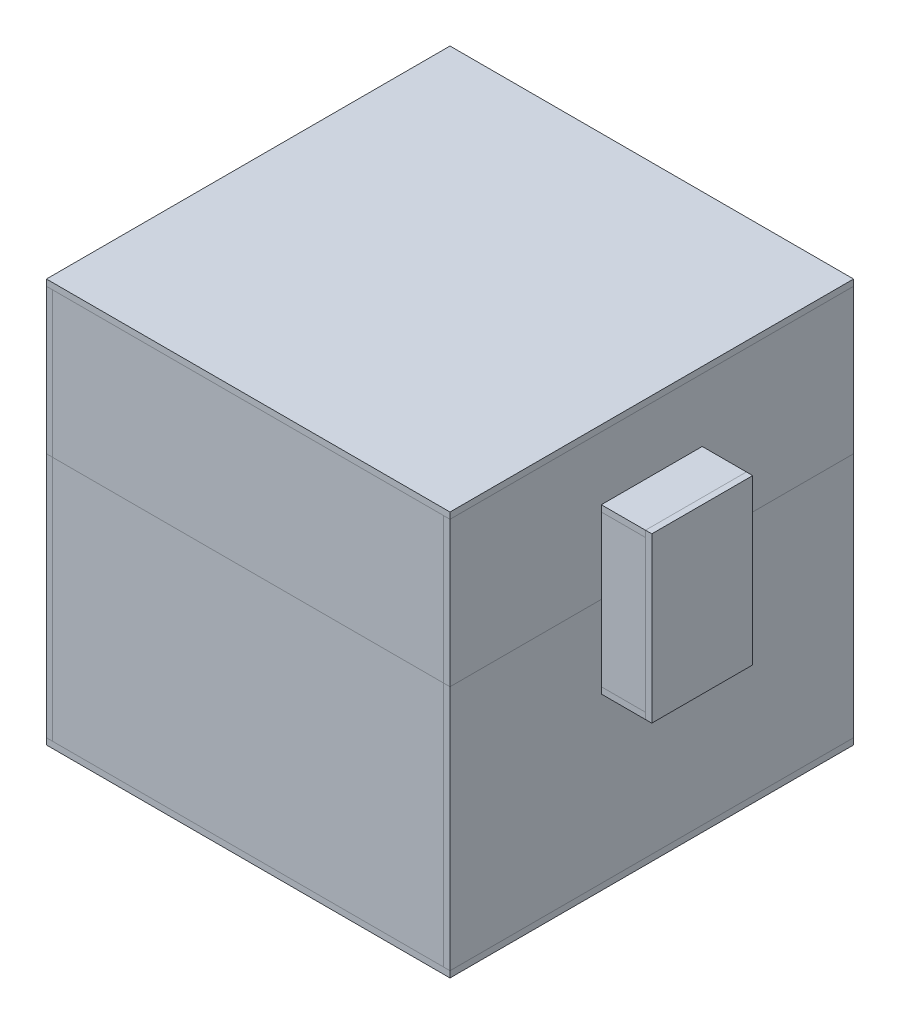
SolidWorks part; units mm, degrees
ref_plane "Front Plane" through (0, 0, 0) normal (0, 0, 1) x (1, 0, 0)
ref_plane "Top Plane" through (0, 0, 0) normal (0, 1, 0) x (1, 0, 0)
ref_plane "Right Plane" through (0, 0, 0) normal (1, 0, 0) x (0, 0, -1)
sketch "Sketch1" plane through (0, 0, 0) normal (0, 1, 0) x (1, 0, 0)
  line L1 (-101.6, -101.6) -> (101.6, -101.6)
  line L2 (-101.6, -101.6) -> (-101.6, 101.6)
  line L3 (-101.6, 101.6) -> (101.6, 101.6)
  line L4 (101.6, -101.6) -> (101.6, 101.6)
  line L5 (-101.6, -101.6) -> (101.6, 101.6) construction
  line L6 (-101.6, 101.6) -> (101.6, -101.6) construction
  point P0 (0, 0)
  dimension "D1" = 203.2
extrude "Boss-Extrude1" add sketch "Sketch1" along normal blind 127
sketch "Sketch2" plane through (0, 127, 0) normal (0, 1, 0) x (1, 0, 0)
  line L20 (95.25, -95.25) -> (95.25, 95.25)
  line L21 (95.25, 95.25) -> (-95.25, 95.25)
  line L22 (-95.25, 95.25) -> (-95.25, -95.25)
  line L23 (-95.25, -95.25) -> (95.25, -95.25)
  line L24 (95.25, -95.25) -> (95.25, 95.25)
  line L25 (95.25, 95.25) -> (-95.25, 95.25)
  line L26 (-95.25, 95.25) -> (-95.25, -95.25)
  line L27 (-95.25, -95.25) -> (95.25, -95.25)
  dimension "D1" = 6.35
extrude "Cut-Extrude1" cut sketch "Sketch2" against normal blind 120.65
sketch "Sketch3" plane through (0, 127, 0) normal (0, 1, 0) x (1, 0, 0)
  line L0 (-101.6, -101.6) -> (101.6, -101.6) construction
  line L1 (101.6, -101.6) -> (101.6, 101.6) construction
  line L2 (-101.6, 101.6) -> (-101.6, -101.6) construction
  line L3 (101.6, 101.6) -> (-101.6, 101.6) construction
  line L4 (-101.6, -101.6) -> (101.6, -101.6)
  line L5 (101.6, -101.6) -> (101.6, 101.6)
  line L6 (-101.6, 101.6) -> (-101.6, -101.6)
  line L7 (101.6, 101.6) -> (-101.6, 101.6)
extrude "Boss-Extrude2" add sketch "Sketch3" along normal blind 76.2 separate body
ref_plane "Plane1" through (-101.6, 127, 101.6) normal (1, 0, 0) x (0, 0, -1)
sketch "Sketch5" plane through (0, 203.2, 0) normal (0, 1, 0) x (1, 0, 0)
  line L8 (-95.25, 95.25) -> (-95.25, -95.25)
  line L9 (-95.25, -95.25) -> (95.25, -95.25)
  line L10 (95.25, -95.25) -> (95.25, 95.25)
  line L11 (95.25, 95.25) -> (-95.25, 95.25)
  line L12 (-95.25, 95.25) -> (-95.25, -95.25)
  line L13 (-95.25, -95.25) -> (95.25, -95.25)
  line L14 (95.25, -95.25) -> (95.25, 95.25)
  line L15 (95.25, 95.25) -> (-95.25, 95.25)
  dimension "D1" = 6.35
extrude "Cut-Extrude2" cut sketch "Sketch5" against normal blind 69.85 from offset 6.35 offset against normal yes
sketch "Sketch6" plane through (0, 0, 0) normal (1, 0, 0) x (0, 0, -1)
  line L0 (-101.6, 127) -> (101.6, 127) construction
  line L1 (-25.4, 85.725) -> (25.4, 85.725)
  line L2 (-25.4, 85.725) -> (-25.4, 168.275)
  line L3 (-25.4, 168.275) -> (25.4, 168.275)
  line L4 (25.4, 85.725) -> (25.4, 168.275)
  line L5 (-25.4, 85.725) -> (25.4, 168.275) construction
  line L6 (-25.4, 168.275) -> (25.4, 85.725) construction
  point P0 (0, 127)
  dimension "D1" = 50.8
  dimension "D2" = 82.55
extrude "Boss-Extrude3" add sketch "Sketch6" along normal blind 25.4 from surface at 101.6 separate body starting at face at (101.6, 165.1, 0)
sketch "Sketch7" plane through (-101.6, 0, 0) normal (-1, 0, 0) x (0, 0, 1)
  line L0 (-76.2, 140) -> (-49.7, 140) construction
  line L1 (-101.6, 127) -> (101.6, 127) construction
  line L2 (-101.6, 203.2) -> (-101.6, 127) construction
  line L3 (0, -111.76) -> (0, 111.76) construction
  circle A0 centre (-76.2, 140) radius 2.5
  circle A1 centre (-49.7, 140) radius 2.5
  circle A2 centre (49.7, 140) radius 2.5
  circle A3 centre (76.2, 140) radius 2.5
  dimension "D2" = 5
  dimension "D1" = 26.5
  dimension "D3" = 13
  dimension "D4" = 25.4
extrude "Cut-Extrude3" cut sketch "Sketch7" against normal up to next (6.35 mm away)
mirror "Mirror4" about plane through (0, 127, 0) normal (0, -1, 0) of "Cut-Extrude3"
sketch "Sketch9" plane through (101.6, 0, 0) normal (-1, 0, 0) x (0, 0, 1)
  line L8 (-19.05, 161.925) -> (-19.05, 92.075)
  line L9 (-19.05, 92.075) -> (19.05, 92.075)
  line L10 (19.05, 92.075) -> (19.05, 161.925)
  line L11 (19.05, 161.925) -> (-19.05, 161.925)
  line L12 (-19.05, 161.925) -> (-19.05, 92.075)
  line L13 (-19.05, 92.075) -> (19.05, 92.075)
  line L14 (19.05, 92.075) -> (19.05, 161.925)
  line L15 (19.05, 161.925) -> (-19.05, 161.925)
  dimension "D1" = 6.35
extrude "Cut-Extrude4" cut sketch "Sketch9" against normal blind 19.05 contours L12 L13 L14 L15
sketch "Sketch10" plane through (120.65, 0, 0) normal (-1, 0, 0) x (0, 0, 1)
  line L4 (19.05, 161.925) -> (-19.05, 161.925)
  line L5 (-19.05, 161.925) -> (-19.05, 92.075)
  line L6 (-19.05, 92.075) -> (19.05, 92.075)
  line L7 (19.05, 92.075) -> (19.05, 161.925)
  line L8 (19.05, 161.925) -> (-19.05, 161.925) construction
  line L9 (-19.05, 161.925) -> (-19.05, 92.075) construction
  line L10 (-19.05, 92.075) -> (19.05, 92.075) construction
  line L11 (19.05, 92.075) -> (19.05, 161.925) construction
  line L12 (22.225, 165.1) -> (-22.225, 165.1)
  line L13 (-22.225, 165.1) -> (-22.225, 88.9)
  line L14 (-22.225, 88.9) -> (22.225, 88.9)
  line L15 (22.225, 88.9) -> (22.225, 165.1)
  dimension "D1" = 0
  dimension "D2" = 3.175
extrude "Boss-Extrude4" add sketch "Sketch10" along normal blind 22.225 from offset 3.175 separate body offset against normal yes
sketch "Sketch15" plane through (127, 0, 0) normal (1, 0, 0) x (0, 0, -1)
  line L4 (25.4, 85.725) -> (25.4, 168.275)
  line L5 (25.4, 168.275) -> (-25.4, 168.275)
  line L6 (-25.4, 168.275) -> (-25.4, 85.725)
  line L7 (-25.4, 85.725) -> (25.4, 85.725)
  line L8 (25.4, 85.725) -> (25.4, 168.275)
  line L9 (25.4, 168.275) -> (-25.4, 168.275)
  line L10 (-25.4, 168.275) -> (-25.4, 85.725)
  line L11 (-25.4, 85.725) -> (25.4, 85.725)
  dimension "D1" = 0
extrude "Boss-Extrude5" add sketch "Sketch15" against normal blind 3.175 separate body contours L8 L9 L10 L11
sketch "Sketch16" plane through (0, 168.275, 0) normal (0, 1, 0) x (1, 0, 0)
  line L0 (123.825, 25.4) -> (123.825, -25.4) construction
  line L1 (123.825, 25.4) -> (123.825, -25.4)
  line L4 (101.6, 25.4) -> (101.6, -25.4)
  line L5 (101.6, -25.4) -> (127, -25.4)
  line L6 (127, -25.4) -> (127, 25.4)
  line L7 (127, 25.4) -> (101.6, 25.4)
  line L8 (101.6, 25.4) -> (101.6, -25.4)
  line L9 (101.6, -25.4) -> (123.825, -25.4)
  line L11 (123.825, 25.4) -> (101.6, 25.4)
  dimension "D1" = 0
extrude "Boss-Extrude7" add sketch "Sketch16" against normal blind 3.175 separate body contours L8 L9 L1 L11
sketch "Sketch18" plane through (0, 85.725, 0) normal (0, -1, 0) x (1, 0, 0)
  line L4 (101.6, -25.4) -> (123.825, -25.4)
  line L5 (101.6, 25.4) -> (101.6, -25.4)
  line L6 (123.825, 25.4) -> (101.6, 25.4)
  line L7 (123.825, -25.4) -> (123.825, 25.4)
  line L8 (101.6, -25.4) -> (123.825, -25.4)
  line L9 (101.6, 25.4) -> (101.6, -25.4)
  line L10 (123.825, 25.4) -> (101.6, 25.4)
  line L11 (123.825, -25.4) -> (123.825, 25.4)
  dimension "D1" = 0
extrude "Boss-Extrude8" add sketch "Sketch18" against normal blind 3.175 separate body contours L8 L11 L10 L9
sketch "Sketch12" plane through (101.6, 0, 0) normal (-1, 0, 0) x (0, 0, 1)
  line L0 (0, -111.76) -> (0, 111.76) construction
  line L1 (-9.5, 98.425) -> (9.5, 98.425)
  line L2 (-9.5, 98.425) -> (-9.5, 117.425)
  line L3 (-9.5, 117.425) -> (9.5, 117.425)
  line L4 (9.5, 98.425) -> (9.5, 117.425)
  line L5 (-9.5, 98.425) -> (9.5, 117.425) construction
  line L6 (-9.5, 117.425) -> (9.5, 98.425) construction
  line L7 (-19.05, 92.075) -> (19.05, 92.075) construction
  point P0 (0, 107.925)
  dimension "D1" = 19
  dimension "D2" = 6.35
sketch "Sketch13" plane through (101.6, 0, 0) normal (-1, 0, 0) x (0, 0, 1)
  line L0 (0, -111.76) -> (0, 111.76) construction
  line L2 (-9.5, 98.425) -> (9.5, 117.425) construction
  circle A0 centre (0, 107.925) radius 4.25
  point P4 (0, 0)
  dimension "D1" = 8.5
extrude "Cut-Extrude6" cut sketch "Sketch13" against normal blind 3 contours A0
sketch "Sketch19" plane through (0, 0, 25.4) normal (0, 0, 1) x (1, 0, 0)
  line L0 (123.825, 165.1) -> (101.6, 165.1)
  line L1 (101.6, 88.9) -> (123.825, 88.9)
  line L2 (123.825, 165.1) -> (123.825, 88.9)
  line L3 (127, 168.275) -> (127, 85.725) construction
  line L12 (101.6, 168.275) -> (101.6, 85.725)
  line L13 (101.6, 85.725) -> (127, 85.725)
  line L14 (127, 85.725) -> (127, 168.275)
  line L15 (127, 168.275) -> (101.6, 168.275)
  line L16 (101.6, 165.1) -> (101.6, 88.9)
  line L20 (127, 168.275) -> (101.6, 168.275) construction
  line L21 (127, 85.725) -> (101.6, 85.725) construction
  dimension "D2" = 3.175
  dimension "D3" = 3.175
  dimension "D4" = 3.175
  dimension "D1" = 0
sketch "Sketch21" plane through (0, 0, -25.4) normal (0, 0, -1) x (-1, 0, 0)
  line L12 (-101.6, 165.1) -> (-123.825, 165.1)
  line L13 (-101.6, 88.9) -> (-101.6, 165.1)
  line L14 (-123.825, 88.9) -> (-101.6, 88.9)
  line L15 (-123.825, 165.1) -> (-123.825, 88.9)
  line L16 (-101.6, 165.1) -> (-123.825, 165.1)
  line L17 (-101.6, 88.9) -> (-101.6, 165.1)
  line L18 (-123.825, 88.9) -> (-101.6, 88.9)
  line L19 (-123.825, 165.1) -> (-123.825, 88.9)
  dimension "D1" = 0
extrude "Boss-Extrude13" add sketch "Sketch21" against normal blind 3.175 separate body
delete or keep bodies "Body-Delete/Keep 1" type delete bodies bodies 108
sketch "Sketch22" plane through (0, 203.2, 0) normal (0, 1, 0) x (1, 0, 0)
  line L4 (-101.6, 101.6) -> (-101.6, -101.6)
  line L5 (-101.6, -101.6) -> (101.6, -101.6)
  line L6 (101.6, -101.6) -> (101.6, 101.6)
  line L7 (101.6, 101.6) -> (-101.6, 101.6)
  line L8 (-101.6, 101.6) -> (-101.6, -101.6)
  line L9 (-101.6, -101.6) -> (101.6, -101.6)
  line L10 (101.6, -101.6) -> (101.6, 101.6)
  line L11 (101.6, 101.6) -> (-101.6, 101.6)
  dimension "D1" = 0
extrude "Boss-Extrude14" add sketch "Sketch22" against normal blind 3.175 separate body
sketch "Sketch23" plane through (101.6, 0, 0) normal (1, 0, 0) x (0, 0, -1)
  line L0 (101.6, 200.025) -> (-101.6, 200.025)
  line L12 (-101.6, 127) -> (101.6, 127)
  line L13 (101.6, 127) -> (101.6, 203.2)
  line L14 (101.6, 203.2) -> (-101.6, 203.2)
  line L15 (-101.6, 203.2) -> (-101.6, 127)
  line L16 (-101.6, 127) -> (101.6, 127)
  line L17 (101.6, 127) -> (101.6, 200.025)
  line L19 (-101.6, 200.025) -> (-101.6, 127)
  dimension "D1" = 0
extrude "Boss-Extrude16" add sketch "Sketch23" against normal blind 3.175 separate body contours L16 L17 L0 L19
sketch "Sketch24" plane through (-101.6, 0, 0) normal (-1, 0, 0) x (0, 0, 1)
  line L0 (-101.6, 200.025) -> (101.6, 200.025)
  line L4 (-101.6, 127) -> (101.6, 127)
  line L5 (101.6, 127) -> (101.6, 203.2)
  line L6 (101.6, 203.2) -> (-101.6, 203.2)
  line L7 (-101.6, 203.2) -> (-101.6, 127)
  line L8 (-101.6, 127) -> (101.6, 127)
  line L9 (101.6, 127) -> (101.6, 200.025)
  line L11 (-101.6, 200.025) -> (-101.6, 127)
  circle A0 centre (76.2, 140) radius 2.5 construction
  circle A1 centre (49.7, 140) radius 2.5 construction
  circle A2 centre (-49.7, 140) radius 2.5 construction
  circle A3 centre (-76.2, 140) radius 2.5 construction
  circle A4 centre (76.2, 140) radius 2.5
  circle A5 centre (49.7, 140) radius 2.5
  circle A6 centre (-49.7, 140) radius 2.5
  circle A7 centre (-76.2, 140) radius 2.5
  dimension "D1" = 0
extrude "Boss-Extrude17" add sketch "Sketch24" against normal blind 3.175 separate body
sketch "Sketch25" plane through (0, 0, 101.6) normal (0, 0, 1) x (1, 0, 0)
  line L0 (-101.6, 127) -> (101.6, 127) construction
  line L1 (-98.425, 127) -> (-98.425, 200.025) construction
  line L2 (98.425, 200.025) -> (98.425, 127) construction
  line L3 (-101.6, 200.025) -> (101.6, 200.025) construction
  line L4 (-98.425, 127) -> (98.425, 127)
  line L5 (-98.425, 127) -> (-98.425, 200.025)
  line L6 (98.425, 200.025) -> (98.425, 127)
  line L7 (-98.425, 200.025) -> (98.425, 200.025)
extrude "Boss-Extrude18" add sketch "Sketch25" against normal blind 3.175 separate body
sketch "Sketch26" plane through (0, 0, -101.6) normal (0, 0, -1) x (-1, 0, 0)
  line L4 (98.425, 127) -> (98.425, 200.025)
  line L5 (-98.425, 127) -> (98.425, 127)
  line L6 (-98.425, 200.025) -> (-98.425, 127)
  line L7 (98.425, 200.025) -> (-98.425, 200.025)
  line L8 (98.425, 127) -> (98.425, 200.025)
  line L9 (-98.425, 127) -> (98.425, 127)
  line L10 (-98.425, 200.025) -> (-98.425, 127)
  line L11 (98.425, 200.025) -> (-98.425, 200.025)
  dimension "D1" = 0
extrude "Boss-Extrude19" add sketch "Sketch26" against normal blind 3.175 separate body contours L8 L11 L10 L9
delete or keep bodies "Body-Delete/Keep 2" type delete bodies bodies 106
sketch "Sketch27" plane through (0, 0, 0) normal (0, -1, 0) x (1, 0, 0)
  line L4 (101.6, -101.6) -> (101.6, 101.6)
  line L5 (101.6, 101.6) -> (-101.6, 101.6)
  line L6 (-101.6, 101.6) -> (-101.6, -101.6)
  line L7 (-101.6, -101.6) -> (101.6, -101.6)
  line L8 (101.6, -101.6) -> (101.6, 101.6)
  line L9 (101.6, 101.6) -> (-101.6, 101.6)
  line L10 (-101.6, 101.6) -> (-101.6, -101.6)
  line L11 (-101.6, -101.6) -> (101.6, -101.6)
  dimension "D1" = 0
extrude "Boss-Extrude20" add sketch "Sketch27" against normal blind 3.175 separate body
sketch "Sketch28" plane through (101.6, 0, 0) normal (1, 0, 0) x (0, 0, -1)
  line L0 (-101.6, 3.175) -> (101.6, 3.175)
  line L4 (-101.6, 0) -> (101.6, 0)
  line L5 (101.6, 0) -> (101.6, 127)
  line L6 (101.6, 127) -> (-101.6, 127)
  line L7 (-101.6, 127) -> (-101.6, 0)
  line L9 (101.6, 3.175) -> (101.6, 127)
  line L10 (101.6, 127) -> (-101.6, 127)
  line L11 (-101.6, 127) -> (-101.6, 3.175)
  dimension "D1" = 0
extrude "Boss-Extrude21" add sketch "Sketch28" against normal blind 3.175 separate body
sketch "Sketch29" plane through (-101.6, 0, 0) normal (-1, 0, 0) x (0, 0, 1)
  line L4 (101.6, 3.175) -> (101.6, 127)
  line L5 (101.6, 127) -> (-101.6, 127)
  line L6 (-101.6, 127) -> (-101.6, 3.175)
  line L7 (-101.6, 3.175) -> (101.6, 3.175)
  line L8 (101.6, 3.175) -> (101.6, 127)
  line L9 (101.6, 127) -> (-101.6, 127)
  line L10 (-101.6, 127) -> (-101.6, 3.175)
  line L11 (-101.6, 3.175) -> (101.6, 3.175)
  circle A0 centre (76.2, 114) radius 2.5 construction
  circle A1 centre (49.7, 114) radius 2.5 construction
  circle A2 centre (-49.7, 114) radius 2.5 construction
  circle A3 centre (-76.2, 114) radius 2.5 construction
  circle A4 centre (76.2, 114) radius 2.5
  circle A5 centre (49.7, 114) radius 2.5
  circle A6 centre (-49.7, 114) radius 2.5
  circle A7 centre (-76.2, 114) radius 2.5
  dimension "D1" = 0
extrude "Boss-Extrude22" add sketch "Sketch29" against normal blind 3.175 separate body
sketch "Sketch30" plane through (0, 0, 101.6) normal (0, 0, 1) x (1, 0, 0)
  line L0 (101.6, 3.175) -> (-101.6, 3.175) construction
  line L1 (98.425, 127) -> (98.425, 3.175) construction
  line L2 (-98.425, 127) -> (98.425, 127) construction
  line L3 (-98.425, 3.175) -> (-98.425, 127) construction
  line L4 (98.425, 3.175) -> (-98.425, 3.175)
  line L5 (98.425, 127) -> (98.425, 3.175)
  line L6 (-98.425, 127) -> (98.425, 127)
  line L7 (-98.425, 3.175) -> (-98.425, 127)
extrude "Boss-Extrude23" add sketch "Sketch30" against normal blind 3.175 separate body
sketch "Sketch31" plane through (0, 0, -101.6) normal (0, 0, -1) x (-1, 0, 0)
  line L4 (98.425, 127) -> (-98.425, 127)
  line L5 (98.425, 3.175) -> (98.425, 127)
  line L6 (-98.425, 3.175) -> (98.425, 3.175)
  line L7 (-98.425, 127) -> (-98.425, 3.175)
  line L8 (98.425, 127) -> (-98.425, 127)
  line L9 (98.425, 3.175) -> (98.425, 127)
  line L10 (-98.425, 3.175) -> (98.425, 3.175)
  line L11 (-98.425, 127) -> (-98.425, 3.175)
  dimension "D1" = 0
extrude "Boss-Extrude24" add sketch "Sketch31" against normal blind 3.175 separate body
delete or keep bodies "Body-Delete/Keep 3" type delete bodies bodies 107
extrude "Boss-Extrude26" add sketch "Sketch19" against normal blind 3.175 separate body
